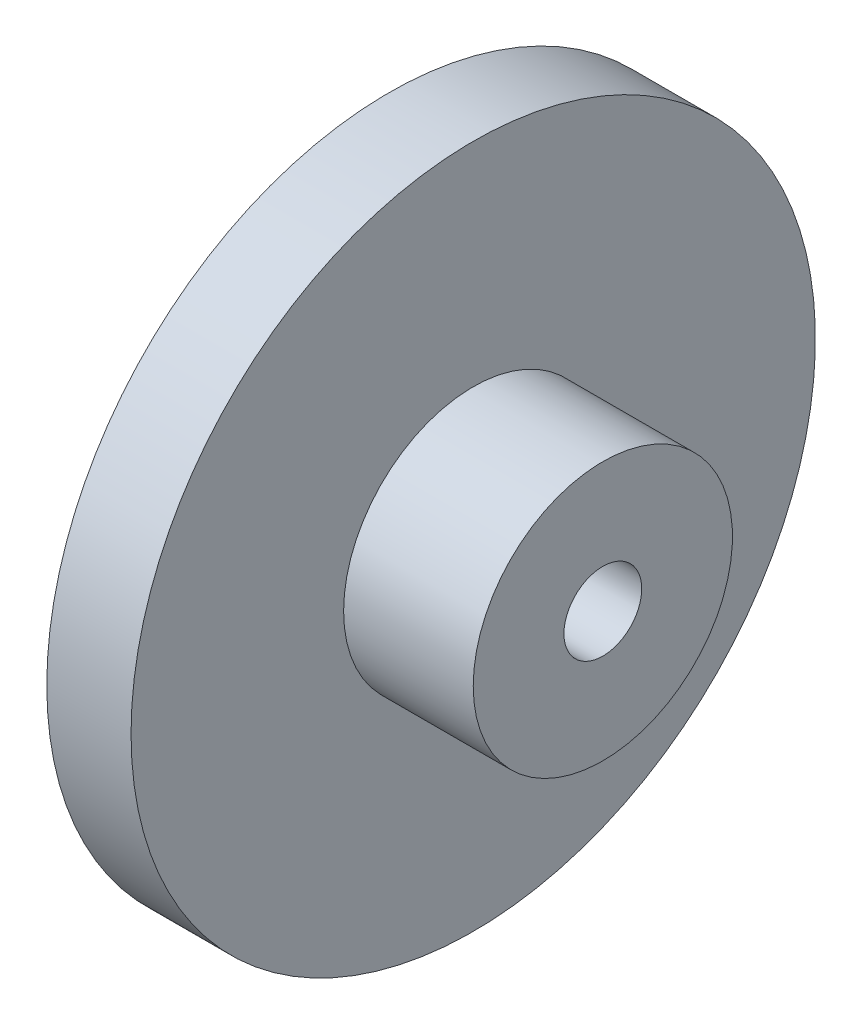
SolidWorks part; units mm, degrees
material "Brass"
ref_plane "Front Plane" through (0, 0, 0) normal (0, 0, 1) x (1, 0, 0)
ref_plane "Top Plane" through (0, 0, 0) normal (0, 1, 0) x (1, 0, 0)
ref_plane "Right Plane" through (0, 0, 0) normal (1, 0, 0) x (0, 0, -1)
sketch "Sketch1" plane through (0, 0, 0) normal (0, 1, 0) x (1, 0, 0)
  line L0 (-31.6089, 0) -> (66.0175, 0) construction
  line L3 (0, 3) -> (0, 26.4)
  line L4 (0, 26.4) -> (6.5, 26.4)
  line L5 (6.5, 26.4) -> (6.5, 10)
  line L6 (6.5, 10) -> (16.5, 10)
  line L7 (16.5, 10) -> (16.5, 3)
  line L8 (16.5, 3) -> (0, 3)
  point P4 (3.6083, 3)
  point P5 (3.6083, 3.6457)
  point P6 (0, 3)
  point P12 (0, 3)
  point P13 (10.3452, 10)
  dimension "D1" = 26.4
  dimension "D2" = 3
  dimension "D3" = 10
  dimension "D4" = 10
  dimension "D5" = 16.5
revolve "Revolve1" add sketch "Sketch1" angle 360 about L0
